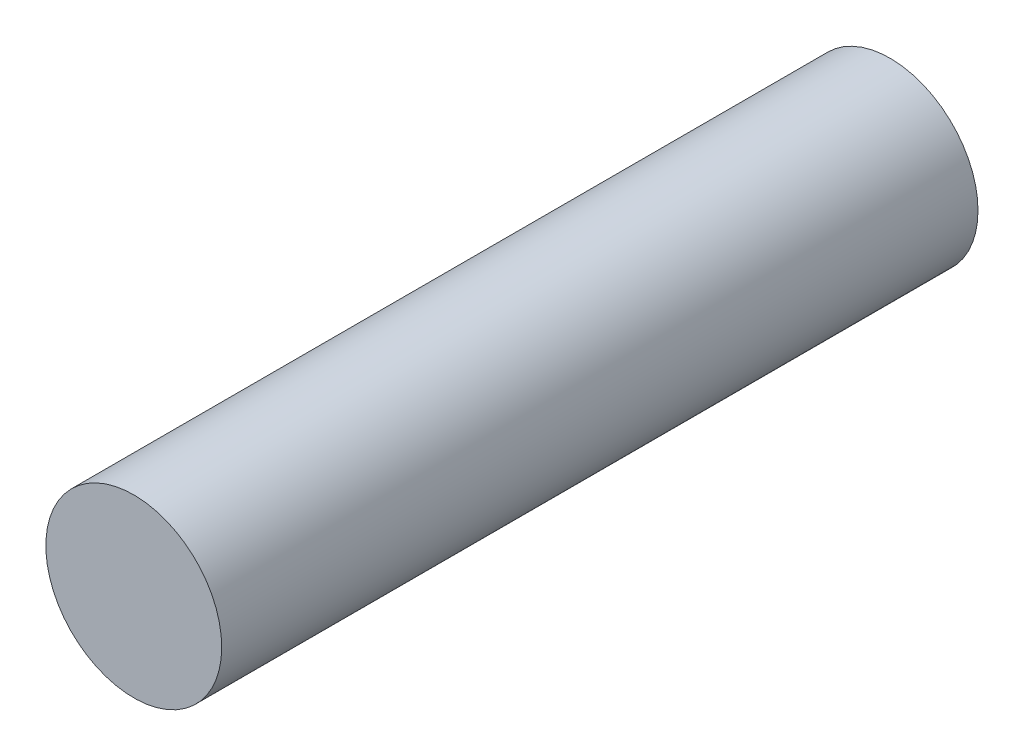
SolidWorks part; units mm, degrees
ref_plane "Front Plane" through (0, 0, 0) normal (0, 0, 1) x (1, 0, 0)
ref_plane "Top Plane" through (0, 0, 0) normal (0, 1, 0) x (1, 0, 0)
ref_plane "Right Plane" through (0, 0, 0) normal (1, 0, 0) x (0, 0, -1)
sketch "Sketch1" plane through (0, 0, 0) normal (0, 0, 1) x (1, 0, 0)
  circle A0 centre (0, 0) radius 5
  dimension "D1" = 10
extrude "Boss-Extrude1" add sketch "Sketch1" along normal blind 43
